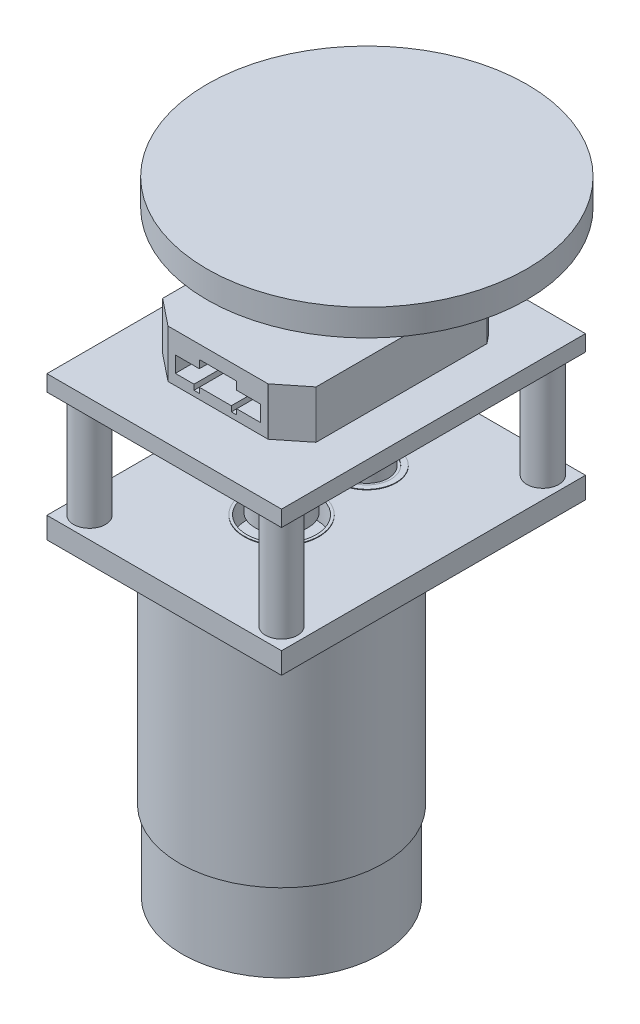
SolidWorks part; units mm, degrees
ref_plane "正面" through (0, 0, 0) normal (0, 0, 1) x (1, 0, 0)
ref_plane "平面" through (0, 0, 0) normal (0, 1, 0) x (1, 0, 0)
ref_plane "右側面" through (0, 0, 0) normal (1, 0, 0) x (0, 0, -1)
sketch "ｽｹｯﾁ1" plane through (0, 0, 0) normal (0, 1, 0) x (1, 0, 0)
  circle A0 centre (0, 0) radius 18.6
  dimension "D1" = 37.2
extrude "ﾎﾞｽ - 押し出し1" add sketch "ｽｹｯﾁ1" along normal blind 15
sketch "ｽｹｯﾁ2" plane through (0, 15, 0) normal (0, 1, 0) x (1, 0, 0)
  circle A0 centre (0, 0) radius 19.1
  dimension "D1" = 38.2
extrude "ﾎﾞｽ - 押し出し2" add sketch "ｽｹｯﾁ2" along normal blind 43
fillet "ﾌｨﾚｯﾄ4" radius 1 1 edges at (0, 58, 19.1)
sketch "ｽｹｯﾁ3" plane through (0, 0, 0) normal (0, -1, 0) x (1, 0, 0)
  circle A0 centre (0, 0) radius 18.1
  dimension "D1" = 36.2
extrude "ｶｯﾄ - 押し出し1" cut sketch "ｽｹｯﾁ3" against normal blind 1
sketch "ｽｹｯﾁ4" plane through (0, 1, 0) normal (0, -1, 0) x (1, 0, 0)
  circle A0 centre (0, 0) radius 7.3
  dimension "D1" = 14.6
extrude "ﾎﾞｽ - 押し出し3" add sketch "ｽｹｯﾁ4" along normal blind 5.7
fillet "ﾌｨﾚｯﾄ5" radius 1 1 edges at (0, -4.7, -7.3)
sketch "ｽｹｯﾁ5" plane through (0, -4.7, 0) normal (0, -1, 0) x (1, 0, 0)
  circle A0 centre (0, 0) radius 4
  dimension "D1" = 8
extrude "ｶｯﾄ - 押し出し2" cut sketch "ｽｹｯﾁ5" against normal blind 2
sketch "ｽｹｯﾁ6" plane through (0, -2.7, 0) normal (0, -1, 0) x (1, 0, 0)
  circle A0 centre (0, 0) radius 2.25
  dimension "D1" = 4.5
extrude "ﾎﾞｽ - 押し出し4" add sketch "ｽｹｯﾁ6" along normal blind 2
sketch "ｽｹｯﾁ7" plane through (0, 58, 0) normal (0, 1, 0) x (1, 0, 0)
  circle A0 centre (0, 0) radius 7
  dimension "D1" = 14
extrude "ﾎﾞｽ - 押し出し5" add sketch "ｽｹｯﾁ7" along normal blind 4.1
sketch "ｽｹｯﾁ8" plane through (0, 62.1, 0) normal (0, 1, 0) x (1, 0, 0)
  circle A0 centre (0, 0) radius 6.5
  dimension "D1" = 13
extrude "ｶｯﾄ - 押し出し3" cut sketch "ｽｹｯﾁ8" against normal blind 2.6
sketch "ｽｹｯﾁ9" plane through (0, 59.5, 0) normal (0, 1, 0) x (1, 0, 0)
  circle A0 centre (0, 0) radius 2.5
  dimension "D1" = 5
extrude "ﾎﾞｽ - 押し出し6" add sketch "ｽｹｯﾁ9" along normal blind 3
sketch "ｽｹｯﾁ10" plane through (0, 62.5, 0) normal (0, 1, 0) x (1, 0, 0)
  circle A0 centre (0, 0) radius 5
  dimension "D1" = 10
extrude "ﾎﾞｽ - 押し出し7" add sketch "ｽｹｯﾁ10" along normal blind 19
sketch "ｽｹｯﾁ12" plane through (0, 58, 0) normal (0, 1, 0) x (1, 0, 0)
  line L1 (-22, 35) -> (22, 35)
  line L2 (-22, 35) -> (-22, -22)
  line L3 (-22, -22) -> (22, -22)
  line L4 (22, 35) -> (22, -22)
  dimension "D1" = 44
  dimension "D2" = 57
extrude "ﾎﾞｽ - 押し出し8" add sketch "ｽｹｯﾁ12" along normal blind 4
sketch "ｽｹｯﾁ13" plane through (0, 62, 0) normal (0, 1, 0) x (1, 0, 0)
  circle A0 centre (-18, 31) radius 3
  dimension "D1" = 6
extrude "ﾎﾞｽ - 押し出し9" add sketch "ｽｹｯﾁ13" along normal blind 20
sketch "ｽｹｯﾁ14" plane through (0, 62, 0) normal (0, 1, 0) x (1, 0, 0)
  circle A0 centre (-18, -18) radius 3
  dimension "D1" = 6
extrude "ﾎﾞｽ - 押し出し10" add sketch "ｽｹｯﾁ14" along normal blind 20
sketch "ｽｹｯﾁ15" plane through (0, 62, 0) normal (0, 1, 0) x (1, 0, 0)
  circle A0 centre (18, 31) radius 3
  dimension "D1" = 6
extrude "ﾎﾞｽ - 押し出し11" add sketch "ｽｹｯﾁ15" along normal blind 20
sketch "ｽｹｯﾁ16" plane through (0, 62, 0) normal (0, 1, 0) x (1, 0, 0)
  circle A0 centre (18, -18) radius 3
  dimension "D1" = 6
extrude "ﾎﾞｽ - 押し出し12" add sketch "ｽｹｯﾁ16" along normal blind 20
sketch "ｽｹｯﾁ17" plane through (0, 82, 0) normal (0, 1, 0) x (1, 0, 0)
  line L1 (-22, 35) -> (22, 35)
  line L2 (-22, 35) -> (-22, -22)
  line L3 (-22, -22) -> (22, -22)
  line L4 (22, 35) -> (22, -22)
extrude "ﾎﾞｽ - 押し出し13" add sketch "ｽｹｯﾁ17" along normal blind 3
sketch "ｽｹｯﾁ21" plane through (0, 62, 0) normal (0, 1, 0) x (1, 0, 0)
  circle A0 centre (0, 0) radius 2.5
  circle A1 centre (0, 0) radius 6.5
extrude "ｶｯﾄ - 押し出し5" cut sketch "ｽｹｯﾁ21" against normal blind 4
sketch "ｽｹｯﾁ22" plane through (0, 85, 0) normal (0, 1, 0) x (1, 0, 0)
  circle A0 centre (0, 0) radius 7
  dimension "D1" = 14
extrude "ｶｯﾄ - 押し出し6" cut sketch "ｽｹｯﾁ22" against normal blind 4
sketch "ｽｹｯﾁ23" plane through (0, 62, 0) normal (0, 1, 0) x (1, 0, 0)
  circle A0 centre (0, 16) radius 5.5
  circle A1 centre (0, 16) radius 4.5
  dimension "D1" = 11
  dimension "D2" = 9
extrude "ﾎﾞｽ - 押し出し14" add sketch "ｽｹｯﾁ23" along normal blind 0.1
sketch "ｽｹｯﾁ24" plane through (0, 62, 0) normal (0, 1, 0) x (1, 0, 0)
  circle A0 centre (0, 16) radius 4
  dimension "D1" = 8
extrude "ﾎﾞｽ - 押し出し15" add sketch "ｽｹｯﾁ24" along normal blind 10
sketch "ｽｹｯﾁ25" plane through (0, 72, 0) normal (0, 1, 0) x (1, 0, 0)
  circle A0 centre (0, 16) radius 5
  dimension "D1" = 10
extrude "ﾎﾞｽ - 押し出し16" add sketch "ｽｹｯﾁ25" along normal blind 3.5
sketch "ｽｹｯﾁ28" plane through (0, 75.5, 0) normal (0, 1, 0) x (1, 0, 0)
  circle A0 centre (0, 16) radius 10.9
extrude "ﾎﾞｽ - 押し出し22" add sketch "ｽｹｯﾁ28" along normal blind 2 contours A0
sketch "ｽｹｯﾁ29" plane through (0, 77.5, 0) normal (0, 1, 0) x (1, 0, 0)
  circle A0 centre (0, 16) radius 4
  dimension "D1" = 8
extrude "ﾎﾞｽ - 押し出し23" add sketch "ｽｹｯﾁ29" along normal blind 4.5
sketch "ｽｹｯﾁ31" plane through (0, 82, 0) normal (0, -1, 0) x (1, 0, 0)
  circle A0 centre (0, -16) radius 5.5
  circle A1 centre (0, -16) radius 4.5
  dimension "D1" = 11
  dimension "D2" = 9
extrude "ﾎﾞｽ - 押し出し25" add sketch "ｽｹｯﾁ31" along normal blind 0.1
sketch "ｽｹｯﾁ32" plane through (0, 85, 0) normal (0, 1, 0) x (1, 0, 0)
  line L0 (-14.38, 23.7209) -> (-14.38, 14.1396)
  line L1 (14.39, -11.9134) -> (-14.38, -11.9134)
  line L2 (14.39, -11.9134) -> (14.39, 14.1396)
  line L4 (-14.38, -11.9134) -> (-14.38, 14.1396)
  line L5 (14.39, 24.1293) -> (14.39, 14.1396)
  arc A0 (-14.38, 23.7209) -> (14.39, 24.1293) centre (0.1468, 13.9385) cw
  dimension "D1" = 28.77
  dimension "D2" = 26.053
extrude "ﾎﾞｽ - 押し出し26" add sketch "ｽｹｯﾁ32" along normal blind 9 contours L1 L4 L0 A0 L5 L2
sketch "ｽｹｯﾁ35" plane through (0, 94, 0) normal (0, 1, 0) x (1, 0, 0)
  line L3 (14.39, -11.9134) -> (-14.38, -11.9134) construction
  line L5 (14.39, -11.9134) -> (14.39, -7.9134)
  line L7 (14.39, -11.9134) -> (14.39, 24.1293) construction
  line L8 (14.39, -7.9134) -> (9.39, -11.9134)
  line L9 (9.39, -11.9134) -> (14.39, -11.9134)
  dimension "D3" = 4
  dimension "D4" = 5
extrude "ｶｯﾄ - 押し出し7" cut sketch "ｽｹｯﾁ35" against normal blind 9 contours L8 L9 L5
sketch "ｽｹｯﾁ37" plane through (0, 94, 0) normal (0, 1, 0) x (1, 0, 0)
  line L0 (-14.38, -11.9134) -> (-9.38, -11.9134)
  line L1 (9.39, -11.9134) -> (-14.38, -11.9134) construction
  line L2 (-9.38, -11.9134) -> (-14.38, -7.9134)
  line L3 (-14.38, 23.7209) -> (-14.38, -11.9134) construction
  line L4 (-14.38, -7.9134) -> (-14.38, -11.9134)
  dimension "D1" = 4
  dimension "D2" = 5
extrude "ｶｯﾄ - 押し出し8" cut sketch "ｽｹｯﾁ37" against normal blind 9
sketch "ｽｹｯﾁ38" plane through (0, 94, 0) normal (0, 1, 0) x (1, 0, 0)
  point P0 (0, 16)
sketch "ｽｹｯﾁ39" plane through (0, 94, 0) normal (0, 1, 0) x (1, 0, 0)
  circle A0 centre (0, 16) radius 2.75
  dimension "D1" = 5.5
extrude "ﾎﾞｽ - 押し出し27" add sketch "ｽｹｯﾁ39" along normal blind 15
sketch "ｽｹｯﾁ40" plane through (0, 0, 11.9134) normal (0, 0, 1) x (1, 0, 0)
  line L1 (-8, 90) -> (-3.5, 90)
  line L2 (-8, 90) -> (-8, 87)
  line L3 (-8, 87) -> (8, 87)
  line L4 (8, 90) -> (8, 87)
  line L5 (3.5, 90) -> (8, 90)
  line L6 (-3.5, 91.5) -> (3.5, 91.5)
  line L7 (-3.5, 91.5) -> (-3.5, 90)
  line L9 (3.5, 91.5) -> (3.5, 90)
  dimension "D1" = 3
  dimension "D2" = 16
  dimension "D3" = 7
  dimension "D4" = 1.5
extrude "ｶｯﾄ - 押し出し9" cut sketch "ｽｹｯﾁ40" against normal blind 9 contours L1 L7 L6 L9 L5 L4 L3 L2
sketch "ｽｹｯﾁ41" plane through (0, 0, 11.9134) normal (0, 0, 1) x (1, 0, 0)
  line L0 (-8, 87) -> (8, 87) construction
  line L1 (3.5, 87) -> (2.5, 87)
  line L2 (3.5, 87) -> (3.5, 86)
  line L3 (3.5, 86) -> (2.5, 86)
  line L4 (2.5, 87) -> (2.5, 86)
  dimension "D1" = 1
  dimension "D2" = 1
extrude "ｶｯﾄ - 押し出し10" cut sketch "ｽｹｯﾁ41" against normal blind 9
sketch "ｽｹｯﾁ42" plane through (0, 0, 11.9134) normal (0, 0, 1) x (1, 0, 0)
  line L0 (-8, 87) -> (2.5, 87) construction
  line L1 (-3.5, 87) -> (-4.5, 87)
  line L2 (-3.5, 87) -> (-3.5, 86)
  line L3 (-3.5, 86) -> (-4.5, 86)
  line L4 (-4.5, 87) -> (-4.5, 86)
  dimension "D1" = 1
  dimension "D2" = 1
extrude "ｶｯﾄ - 押し出し11" cut sketch "ｽｹｯﾁ42" against normal blind 9
fillet "ﾌｨﾚｯﾄ6" radius 0.01 1 edges at (0, 109, -13.25)
fillet "ﾌｨﾚｯﾄ7" radius 0.1 6 edges at (-9.38, 89.5, 11.9134) (-14.38, 89.5, 7.9134) (9.39, 89.5, 11.9134) (14.39, 89.5, 7.9134) (-14.38, 89.5, -23.7209) (14.39, 89.5, -24.1293)
sketch "ｽｹｯﾁ43" plane through (0, 94, 0) normal (0, 1, 0) x (1, 0, 0)
  circle A0 centre (0, 16) radius 7.5
  circle A1 centre (0, 16) radius 7
  dimension "D1" = 15
  dimension "D2" = 14
extrude "ｶｯﾄ - 押し出し12" cut sketch "ｽｹｯﾁ43" against normal blind 3
sketch "ｽｹｯﾁ44" plane through (0, 109, 0) normal (0, 1, 0) x (1, 0, 0)
  circle A0 centre (0, 16) radius 30
  dimension "D1" = 60
extrude "ﾎﾞｽ - 押し出し28" add sketch "ｽｹｯﾁ44" against normal blind 5
